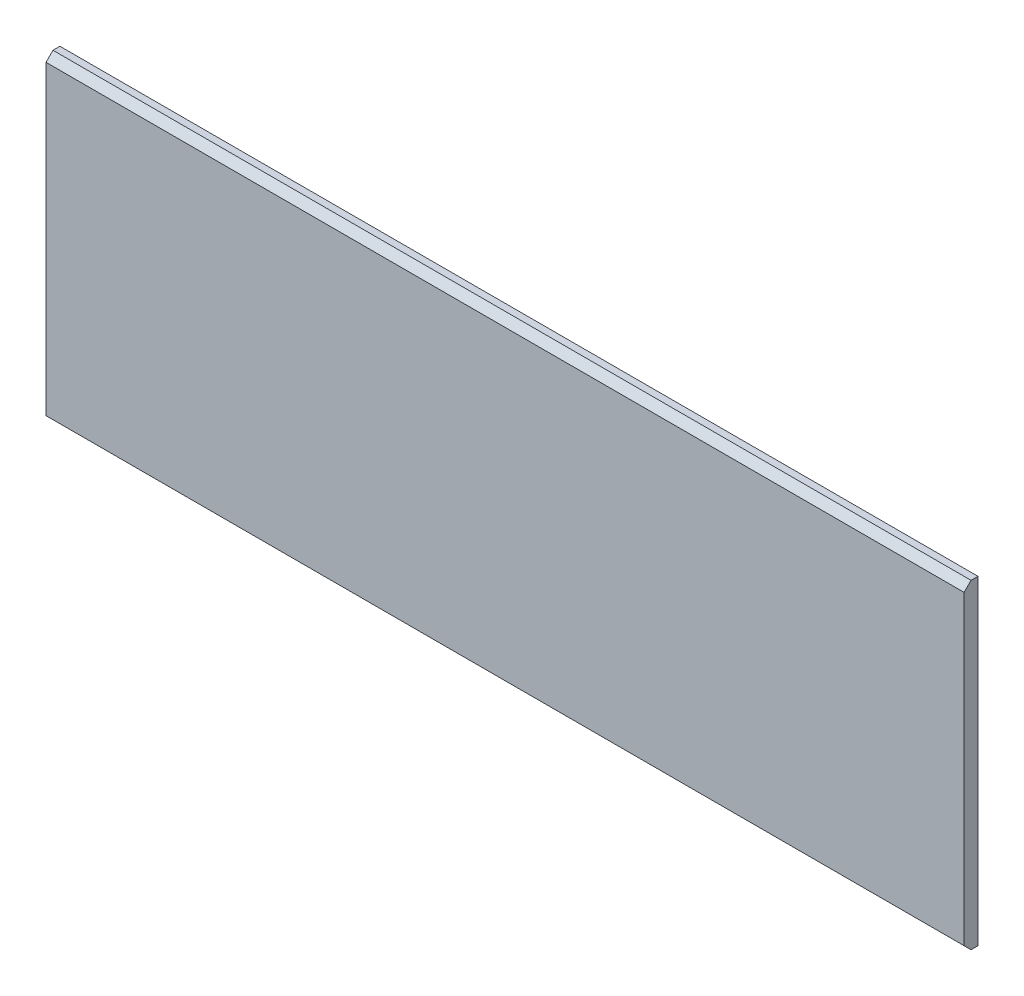
SolidWorks part; units mm, degrees
ref_plane "前视基准面" through (0, 0, 0) normal (0, 0, 1) x (1, 0, 0)
ref_plane "上视基准面" through (0, 0, 0) normal (0, 1, 0) x (1, 0, 0)
ref_plane "右视基准面" through (0, 0, 0) normal (1, 0, 0) x (0, 0, -1)
sketch "草图1" plane through (0, 0, 0) normal (0, 0, 1) x (1, 0, 0)
  line L1 (-330, 115) -> (330, 115)
  line L2 (-330, 115) -> (-330, -115)
  line L3 (-330, -115) -> (330, -115)
  line L4 (330, 115) -> (330, -115)
  line L5 (-330, 115) -> (330, -115) construction
  line L6 (-330, -115) -> (330, 115) construction
  point P0 (0, 0)
  dimension "D1" = 660
  dimension "D2" = 230
extrude "凸台-拉伸1" add sketch "草图1" along normal blind 10
chamfer "倒角1" distance 5 angle 45 2 edges at (0, 115, 10) (0, -115, 10)
